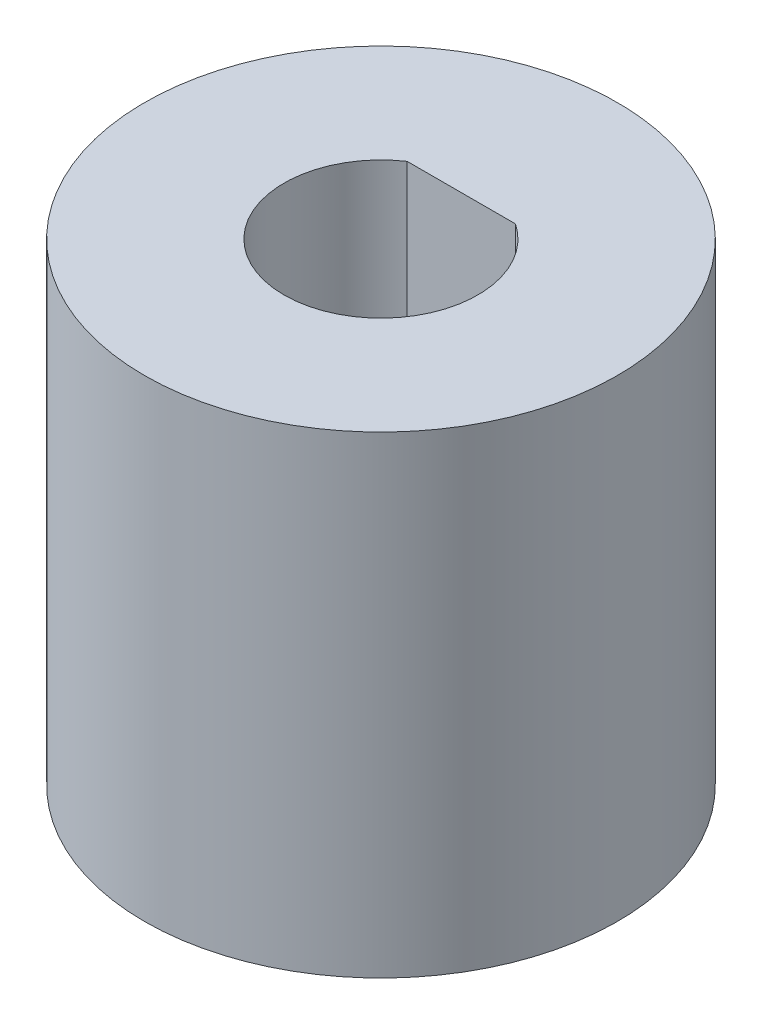
SolidWorks part; units mm, degrees
ref_plane "Front Plane" through (0, 0, 0) normal (0, 0, 1) x (1, 0, 0)
ref_plane "Top Plane" through (0, 0, 0) normal (0, 1, 0) x (1, 0, 0)
ref_plane "Right Plane" through (0, 0, 0) normal (1, 0, 0) x (0, 0, -1)
sketch "Sketch1" plane through (0, 0, 0) normal (0, 1, 0) x (1, 0, 0)
  circle A0 centre (0, 0) radius 7.5
  dimension "D1" = 15
extrude "Boss-Extrude1" add sketch "Sketch1" along normal blind 15
sketch "Sketch2" plane through (0, 15, 0) normal (0, 1, 0) x (1, 0, 0)
  line L0 (1.7185, 2.55) -> (-1.7185, 2.55)
  arc A0 (-1.7185, 2.55) -> (1.7185, 2.55) centre (0, 0) ccw
  point P3 (0, 0)
  point P5 (0, -3.075)
  dimension "D1" = 3.075
  dimension "D2" = 5.625
extrude "Cut-Extrude1" cut sketch "Sketch2" against normal blind 10
